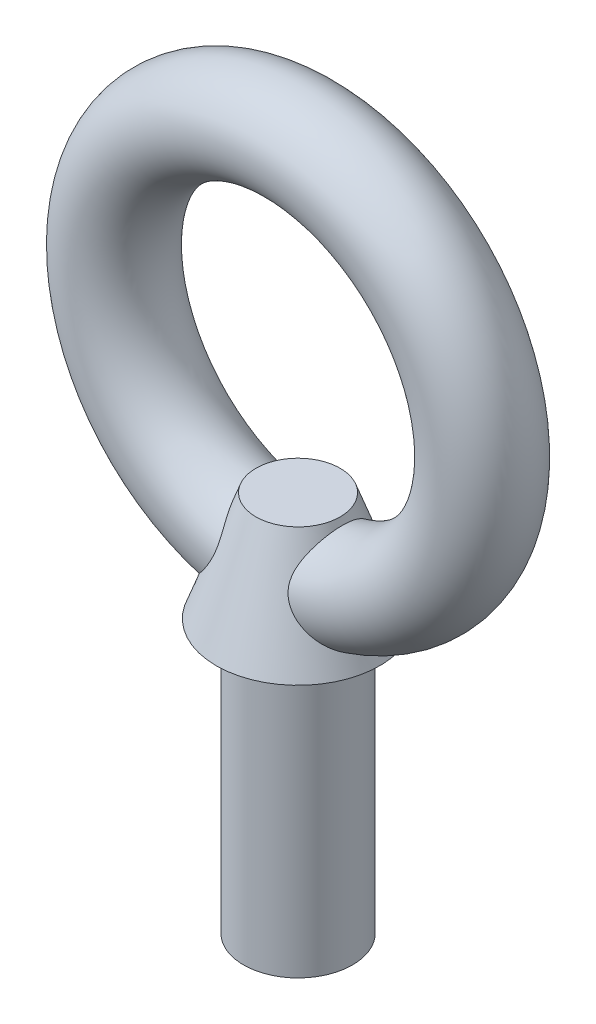
SolidWorks part; units mm, degrees
ref_plane "Plan de face" through (0, 0, 0) normal (0, 0, 1) x (1, 0, 0)
ref_plane "Plan de dessus" through (0, 0, 0) normal (0, 1, 0) x (1, 0, 0)
ref_plane "Plan de droite" through (0, 0, 0) normal (1, 0, 0) x (0, 0, -1)
sketch "Esquisse2" plane through (0, 0, 0) normal (0, 1, 0) x (1, 0, 0)
  line L0 (-6.75, 0) -> (6.75, 0) construction
  line L1 (0, 0) -> (0, 4.38) construction
  circle A0 centre (6.75, 0) radius 1.75
  dimension "D1" = 3.5
  dimension "D2" = 6.75
revolve "Révolution1" add sketch "Esquisse2" angle 360 about L1
sketch "Esquisse3" plane through (0, 0, 0) normal (0, 1, 0) x (1, 0, 0)
  circle A0 centre (0, 0) radius 3
  dimension "D1" = 6
extrude "Boss.-Extru.1" add sketch "Esquisse3" along normal blind 4 draft 20 from offset 8.5 separate body offset against normal yes
sketch "Esquisse4" plane through (0, -8.5, 0) normal (0, -1, 0) x (1, 0, 0)
  circle A0 centre (0, 0) radius 2
  dimension "D1" = 4
extrude "Boss.-Extru.2" add sketch "Esquisse4" along normal blind 10
